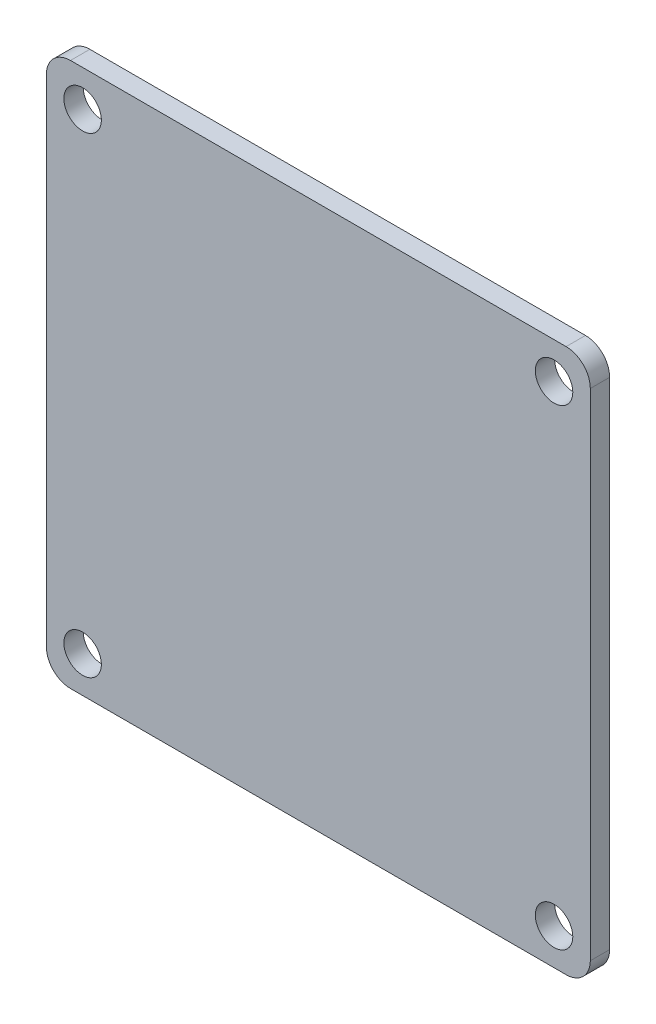
SolidWorks part; units mm, degrees
ref_plane "Ebene vorne" through (0, 0, 0) normal (0, 0, 1) x (1, 0, 0)
ref_plane "Ebene oben" through (0, 0, 0) normal (0, 1, 0) x (1, 0, 0)
ref_plane "Ebene rechts" through (0, 0, 0) normal (1, 0, 0) x (0, 0, -1)
sketch "Skizze1" plane through (0, 0, 0) normal (0, 0, 1) x (1, 0, 0)
  line L1 (0, 0) -> (45, 0)
  line L2 (0, 0) -> (0, 45)
  line L3 (0, 45) -> (45, 45)
  line L4 (45, 0) -> (45, 45)
  line L5 (3, 42) -> (42, 42) construction
  line L6 (42, 42) -> (42, 3) construction
  line L7 (42, 3) -> (3, 3) construction
  line L8 (3, 3) -> (3, 42) construction
  circle A0 centre (3, 42) radius 1.55
  circle A1 centre (42, 42) radius 1.55
  circle A2 centre (42, 3) radius 1.55
  circle A3 centre (3, 3) radius 1.55
  dimension "D3" = 3.1
  dimension "D4" = 3.1
  dimension "D5" = 3.1
  dimension "D6" = 3.1
  dimension "D1" = 45
  dimension "D2" = 45
  dimension "D7" = 3
  dimension "D8" = 3
  dimension "D9" = 3
  dimension "D10" = 3
extrude "Aufsatz-Linear austragen1" add sketch "Skizze1" along normal blind 1.6
fillet "Verrundung1" radius 2 4 edges at (0, 45, 0.8) (45, 45, 0.8) (45, 0, 0.8) (0, 0, 0.8)
